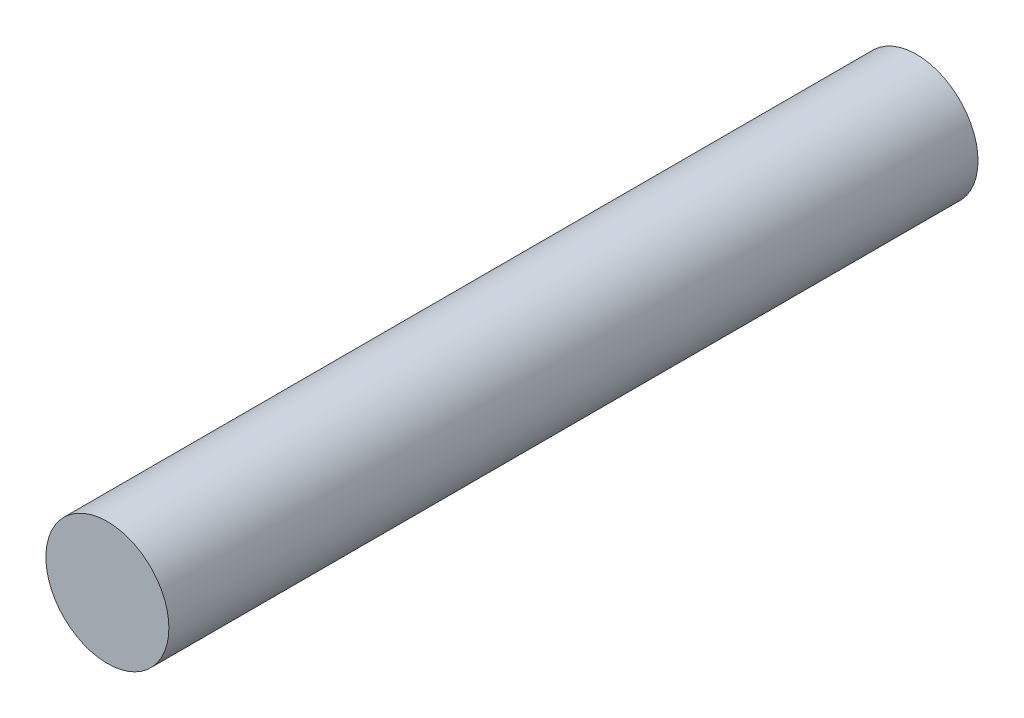
SolidWorks part; units mm, degrees
ref_plane "Front Plane" through (0, 0, 0) normal (0, 0, 1) x (1, 0, 0)
ref_plane "Top Plane" through (0, 0, 0) normal (0, 1, 0) x (1, 0, 0)
ref_plane "Right Plane" through (0, 0, 0) normal (1, 0, 0) x (0, 0, -1)
sketch "Sketch1" plane through (0, 0, 0) normal (0, 0, 1) x (1, 0, 0)
  circle A0 centre (0, 0) radius 1.9
  dimension "D1" = 3.8
extrude "Boss-Extrude1" add sketch "Sketch1" along normal mid plane 25
